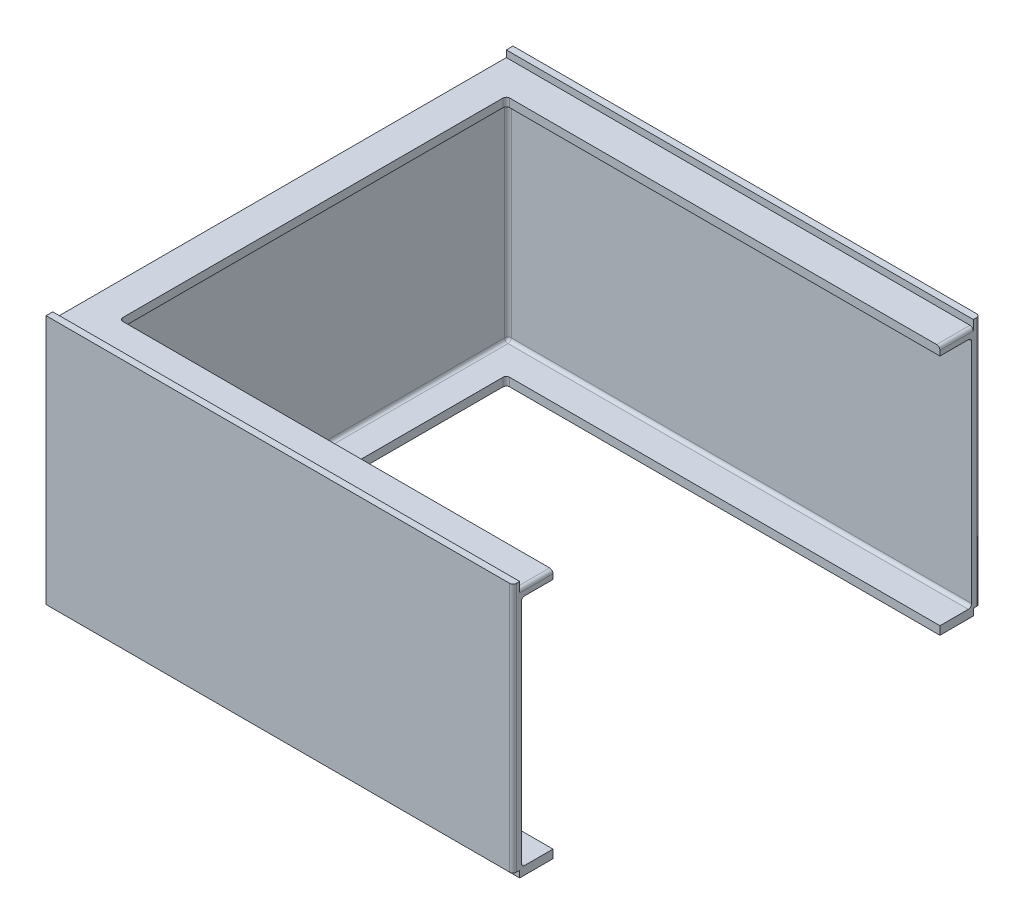
SolidWorks part; units mm, degrees
ref_plane "前视基准面" through (0, 0, 0) normal (0, 0, 1) x (1, 0, 0)
ref_plane "上视基准面" through (0, 0, 0) normal (0, 1, 0) x (1, 0, 0)
ref_plane "右视基准面" through (0, 0, 0) normal (1, 0, 0) x (0, 0, -1)
sketch "草图1" plane through (0, 0, 0) normal (0, 1, 0) x (1, 0, 0)
  line L1 (140, -140) -> (-140, -140)
  line L2 (140, -140) -> (140, 140)
  line L3 (140, 140) -> (-140, 140)
  line L4 (-140, -140) -> (-140, 140)
  line L5 (140, -140) -> (-140, 140) construction
  line L6 (140, 140) -> (-140, -140) construction
  point P0 (0, 0)
  dimension "D1" = 280
  dimension "D2" = 280
extrude "凸台-拉伸1" add sketch "草图1" along normal blind 154
sketch "草图2" plane through (0, 154, 0) normal (0, 1, 0) x (1, 0, 0)
  line L0 (140, -140) -> (140, 140) construction
  line L1 (140, 140) -> (-140, 140) construction
  line L5 (140, -136) -> (-140, -136)
  line L6 (140, -136) -> (140, 136)
  line L7 (140, 136) -> (-140, 136)
  line L8 (-140, -136) -> (-140, 136)
  line L9 (140, -136) -> (-140, 136) construction
  line L10 (140, 136) -> (-140, -136) construction
  point P0 (0, 0)
  dimension "D1" = 0
  dimension "D2" = 4
extrude "切除-拉伸1" cut sketch "草图2" against normal blind 4
sketch "草图3" plane through (0, 0, 0) normal (0, -1, 0) x (1, 0, 0)
  line L0 (-140, 136) -> (140, 136)
  line L1 (-140, -140) -> (-140, 140) construction
  line L2 (140, 140) -> (140, -140) construction
  line L3 (140, -140) -> (-140, -140) construction
  line L4 (-140, 140) -> (140, 140) construction
  line L5 (140, -140) -> (-140, -140)
  line L6 (140, 140) -> (140, 136)
  line L7 (-140, 140) -> (140, 140)
  line L8 (-140, -140) -> (-140, -136)
  line L9 (-140, -136) -> (140, -136)
  line L10 (-140, 136) -> (-140, 140)
  line L11 (140, -136) -> (140, -140)
  dimension "D1" = 4
  dimension "D2" = 4
extrude "切除-拉伸2" cut sketch "草图3" against normal blind 4
sketch "草图4" plane through (140, 0, 0) normal (1, 0, 0) x (0, 0, -1)
  line L0 (0, 150) -> (0, 0) construction
  line L1 (-136, 150) -> (136, 150) construction
  line L2 (-136, 0) -> (136, 0) construction
  line L6 (140, 154) -> (140, 4) construction
  line L7 (135, 5) -> (-135, 5)
  line L8 (135, 5) -> (135, 145)
  line L9 (135, 145) -> (-135, 145)
  line L10 (-135, 5) -> (-135, 145)
  line L11 (135, 5) -> (-135, 145) construction
  line L12 (135, 145) -> (-135, 5) construction
  point P6 (0, 75)
  point P8 (0, 75)
  dimension "D1" = 5
  dimension "D2" = 5
extrude "切除-拉伸3" cut sketch "草图4" against normal offset from surface (278 mm away) 2 up to face at (-140, 77.6667, 0)
sketch "草图6" plane through (0, 150, 0) normal (0, 1, 0) x (1, 0, 0)
  line L11 (140, -136) -> (140, 136) construction
  line L12 (140, 116) -> (-120, 116)
  line L14 (140, 116) -> (140, -116)
  line L15 (140, -116) -> (-120, -116)
  line L16 (-120, 116) -> (-120, -116)
  line L17 (140, 136) -> (-140, 136) construction
  line L18 (-140, -136) -> (140, -136) construction
  line L19 (-140, 136) -> (-140, -136) construction
  dimension "D1" = 20
  dimension "D2" = 20
  dimension "D3" = 20
extrude "切除-拉伸7" cut sketch "草图6" against normal through all
sketch "草图7" plane through (0, 0, 0) normal (1, 0, 0) x (0, 0, -1)
  line L0 (-135, 145) -> (-135, 5) construction
  line L1 (-135, 119) -> (-135, 115)
  line L2 (-135, 75) -> (135, 75) construction
  line L3 (135, 145) -> (135, 5) construction
  line L4 (0, 145) -> (0, 5) construction
  line L5 (-135, 145) -> (135, 145) construction
  line L6 (135, 5) -> (-135, 5) construction
  line L7 (-135, 119) -> (-134, 119)
  line L8 (-134, 119) -> (-134, 115)
  line L9 (-134, 115) -> (-135, 115)
  line L10 (-134, 35) -> (-135, 35)
  line L11 (-134, 31) -> (-134, 35)
  line L12 (-135, 31) -> (-134, 31)
  line L13 (-135, 31) -> (-135, 35)
  line L14 (135, 31) -> (135, 35)
  line L15 (135, 31) -> (134, 31)
  line L16 (134, 31) -> (134, 35)
  line L17 (134, 35) -> (135, 35)
  line L18 (134, 115) -> (135, 115)
  line L19 (134, 119) -> (134, 115)
  line L20 (135, 119) -> (134, 119)
  line L21 (135, 119) -> (135, 115)
  dimension "D1" = 1
  dimension "D2" = 4
  dimension "D3" = 40
fillet "圆角4" radius 2 2 edges at (140, 79, -140) (140, 79, 140)
fillet "圆角5" radius 2 2 edges at (140, 150, -126) (140, 150, 126)
fillet "圆角6" radius 2 4 edges at (-120, 2.5, 116) (-120, 2.5, -116) (-120, 147.5, -116) (-120, 147.5, 116)
fillet "圆角7" radius 2 8 edges at (-138, 75, -135) (-138, 75, 135) (-138, 145, 0) (-138, 5, 0) (1, 145, -135) (1, 5, -135) (1, 5, 135) (1, 145, 135)
